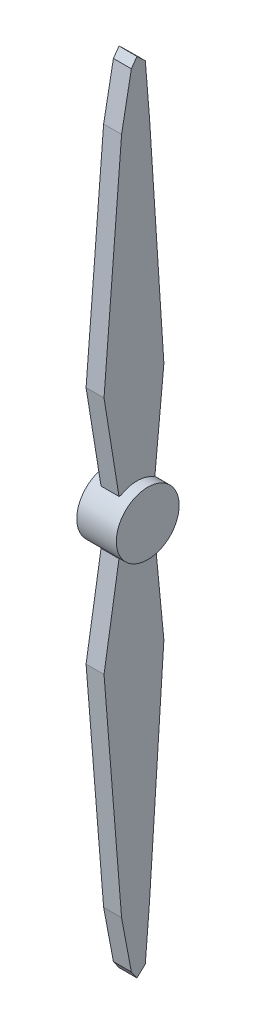
SolidWorks part; units mm, degrees
ref_plane "Front Plane" through (0, 0, 0) normal (0, 0, 1) x (1, 0, 0)
ref_plane "Top Plane" through (0, 0, 0) normal (0, 1, 0) x (1, 0, 0)
ref_plane "Right Plane" through (0, 0, 0) normal (1, 0, 0) x (0, 0, -1)
sketch "Sketch1" plane through (0, 0, 0) normal (1, 0, 0) x (0, 0, -1)
  line L0 (-8.001, 12) -> (-14.6685, 53.34)
  line L1 (-14.6685, 53.34) -> (-6.8453, 151.13)
  line L2 (-6.8453, 151.13) -> (-2.4892, 174.244)
  line L3 (-2.4892, 174.244) -> (0, 177.8)
  line L4 (0, 177.8) -> (3.7338, 174.244)
  line L5 (3.7338, 174.244) -> (5.6007, 151.13)
  line L6 (5.6007, 151.13) -> (12.0015, 53.34)
  line L7 (12.0015, 53.34) -> (8.001, 12)
  line L8 (8.001, 12) -> (-8.001, 12)
  line L9 (-8.001, -12) -> (-14.6685, -53.34)
  line L10 (-14.6685, -53.34) -> (-6.8453, -151.13)
  line L11 (-6.8453, -151.13) -> (-2.4892, -174.244)
  line L12 (-2.4892, -174.244) -> (0, -177.8)
  line L13 (0, -177.8) -> (3.7338, -174.244)
  line L14 (3.7338, -174.244) -> (5.6007, -151.13)
  line L15 (5.6007, -151.13) -> (12.0015, -53.34)
  line L16 (12.0015, -53.34) -> (8.001, -12)
  line L17 (8.001, -12) -> (-8.001, -12)
extrude "Boss-Extrude1" add sketch "Sketch1" along normal mid plane 8
sketch "Sketch2" plane through (0, 0, 0) normal (1, 0, 0) x (0, 0, -1)
  circle A0 centre (0, 0) radius 14
extrude "Boss-Extrude2" add sketch "Sketch2" along normal mid plane 17.6
